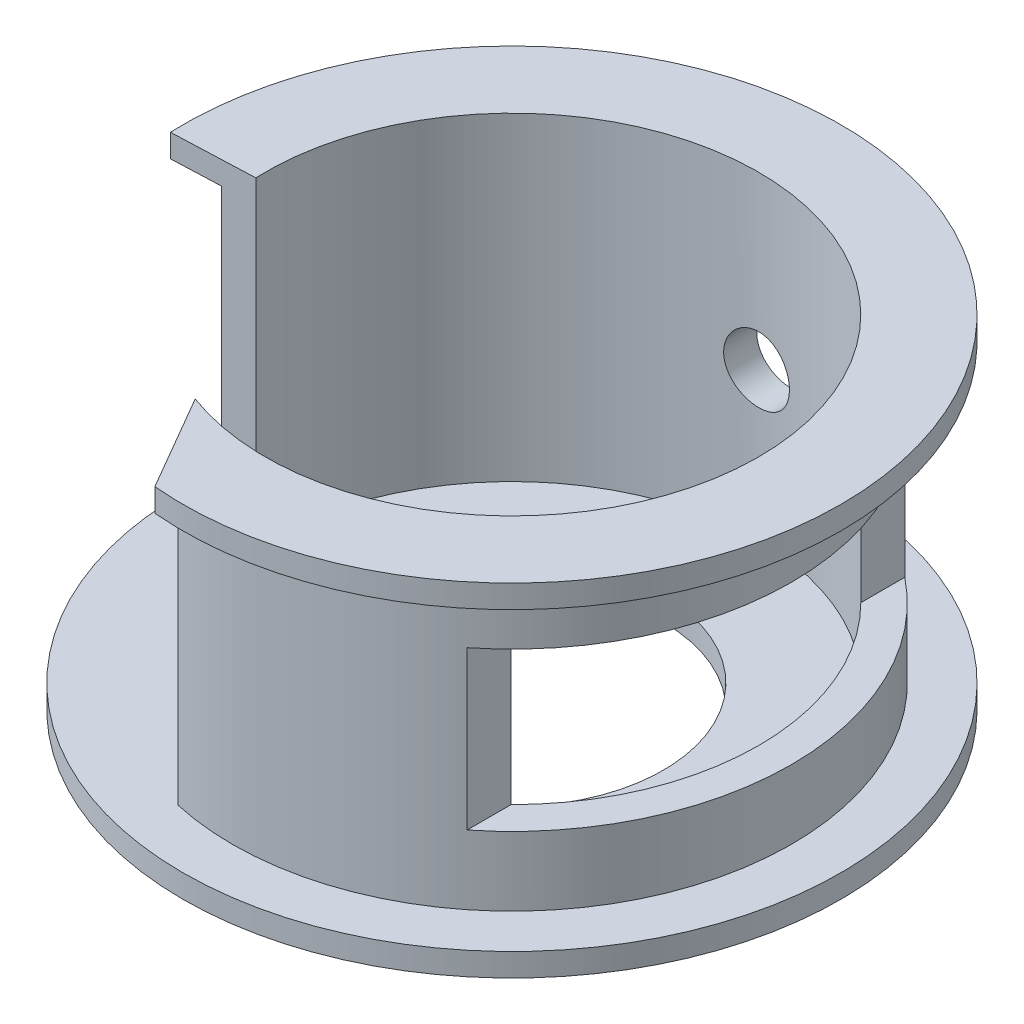
SolidWorks part; units mm, degrees
ref_plane "Front Plane" through (0, 0, 0) normal (0, 0, 1) x (1, 0, 0)
ref_plane "Top Plane" through (0, 0, 0) normal (0, 1, 0) x (1, 0, 0)
ref_plane "Right Plane" through (0, 0, 0) normal (1, 0, 0) x (0, 0, -1)
sketch "Sketch1" plane through (0, 0, 0) normal (0, 1, 0) x (1, 0, 0)
  circle A0 centre (-49.6228, -6.0186) radius 5
extrude "Boss-Extrude1" add sketch "Sketch1" along normal blind 0.35
sketch "Sketch2" plane through (0, 0.35, 0) normal (0, 1, 0) x (1, 0, 0)
  circle A0 centre (-49.6228, -6.0186) radius 4.25
  circle A2 centre (-49.6228, -6.0186) radius 3.75
extrude "Boss-Extrude6" add sketch "Sketch2" along normal blind 4.5 contours A0 | A2
sketch "Sketch5" plane through (0, 4.85, 0) normal (0, 1, 0) x (1, 0, 0)
  circle A0 centre (-49.6228, -6.0186) radius 5
  circle A1 centre (-49.6228, -6.0186) radius 3.75
extrude "Boss-Extrude7" add sketch "Sketch5" along normal blind 0.35
sketch "Sketch9" plane through (0, 0.35, 0) normal (0, 1, 0) x (1, 0, 0)
  circle A0 centre (-49.6228, -6.0186) radius 2.3
extrude "Cut-Extrude5" cut sketch "Sketch9" against normal blind 11.4
sketch "Sketch10" plane through (0, 0, 0) normal (0, 0, 1) x (1, 0, 0)
  line L0 (-46.9777, 2.6) -> (-46.9777, 1.4)
  line L3 (-46.9777, 2.6) -> (-46.9777, 3.8)
  line L5 (-46.9777, 3.8) -> (-43.2058, 3.8)
  line L6 (-46.9777, 3.8) -> (-46.9777, 1.4)
  line L7 (-46.9777, 1.4) -> (-43.2058, 1.4)
  line L8 (-43.2058, 3.8) -> (-43.2058, 1.4)
extrude "Cut-Extrude6" cut sketch "Sketch10" along normal blind 11.4 contours L8 L5 L3 L0 L7
sketch "Sketch11" plane through (0, 5.2, 0) normal (0, 1, 0) x (1, 0, 0)
  line L0 (-54.6189, -6.2146) -> (-53.3699, -6.1656)
  line L1 (-50.9188, -9.5375) -> (-50.071, -10.9985)
  circle A2 centre (-49.6228, -6.0186) radius 3.75
  circle A3 centre (-49.6228, -6.0186) radius 5
  circle M3 centre (-49.6228, -6.0186) radius 5
  circle M4 centre (-49.6228, -6.0186) radius 3.75
extrude "Cut-Extrude8" cut sketch "Sketch11" against normal blind 4.85 contours L1 L0 M4 M3
sketch "Sketch12" plane through (0, 0, 0) normal (0, 0, 1) x (1, 0, 0)
  line L0 (-51.3079, 5.2) -> (-51.3079, 0)
  line L1 (-45.8728, 5.2) -> (-53.3728, 5.2) construction
  line L2 (-54.6228, 0) -> (-44.6228, 0) construction
  line L3 (-53.8695, 4.85) -> (-45.3728, 4.85)
  line L4 (-54.6228, 4.85) -> (-44.6228, 4.85) construction
  line L5 (-45.3728, 3.8) -> (-45.3728, 4.85) construction
  line L6 (-45.3728, 4.85) -> (-49.6211, 4.85)
  circle A0 centre (-51.3079, 2.6) radius 0.5
  circle A1 centre (-49.6211, 2.6) radius 0.5
extrude "Cut-Extrude9" cut sketch "Sketch12" along normal blind 4.85 contours A1
